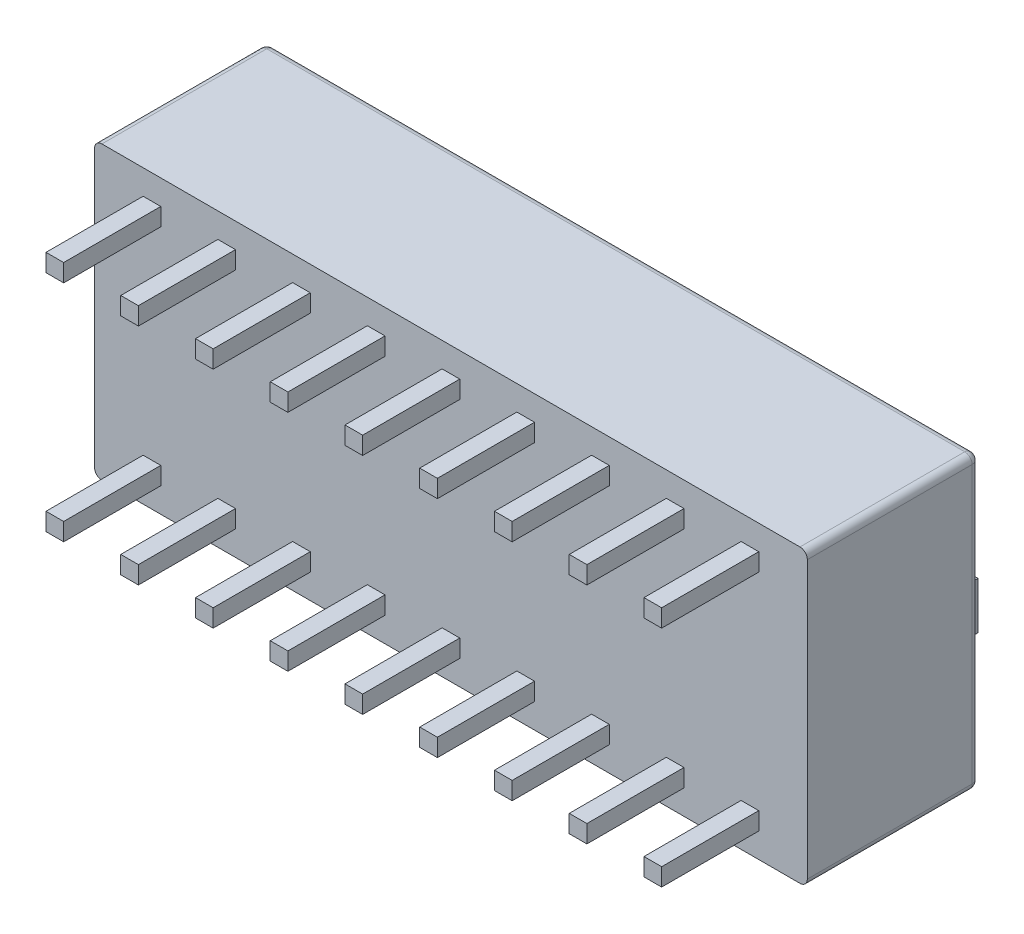
SolidWorks part; units mm, degrees
ref_plane "Ön Düzlem" through (0, 0, 0) normal (0, 0, 1) x (1, 0, 0)
ref_plane "Üst Düzlem" through (0, 0, 0) normal (0, 1, 0) x (1, 0, 0)
ref_plane "Sağ Düzlem" through (0, 0, 0) normal (1, 0, 0) x (0, 0, -1)
sketch "Çizim1" plane through (0, 0, 0) normal (0, 0, 1) x (1, 0, 0)
  line L1 (-12.11, 4.95) -> (12.11, 4.95)
  line L2 (-12.11, 4.95) -> (-12.11, -4.95)
  line L3 (-12.11, -4.95) -> (12.11, -4.95)
  line L4 (12.11, 4.95) -> (12.11, -4.95)
  line L5 (-12.11, 4.95) -> (12.11, -4.95) construction
  line L6 (-12.11, -4.95) -> (12.11, 4.95) construction
  point P0 (0, 0)
extrude "Yükseklik-Ekstrüzyon1" add sketch "Çizim1" along normal blind 5.85
sketch "Çizim3" plane through (0, 0, 0) normal (0, 0, -1) x (-1, 0, 0)
  line L10 (-10.86, 1.6) -> (-9.46, 1.6)
  line L11 (-10.86, 1.6) -> (-10.86, -1.6)
  line L12 (-10.86, -1.6) -> (-9.46, -1.6)
  line L13 (-9.46, 1.6) -> (-9.46, -1.6)
  line L14 (-10.86, 1.6) -> (-9.46, -1.6) construction
  line L15 (-10.86, -1.6) -> (-9.46, 1.6) construction
  line L16 (-8.32, 1.6) -> (-6.92, 1.6)
  line L17 (-8.32, 1.6) -> (-8.32, -1.6)
  line L18 (-8.32, -1.6) -> (-6.92, -1.6)
  line L19 (-6.92, 1.6) -> (-6.92, -1.6)
  line L20 (-8.32, 1.6) -> (-6.92, -1.6) construction
  line L21 (-8.32, -1.6) -> (-6.92, 1.6) construction
  line L22 (-5.78, 1.6) -> (-4.38, 1.6)
  line L23 (-5.78, 1.6) -> (-5.78, -1.6)
  line L24 (-5.78, -1.6) -> (-4.38, -1.6)
  line L25 (-4.38, 1.6) -> (-4.38, -1.6)
  line L26 (-5.78, 1.6) -> (-4.38, -1.6) construction
  line L27 (-5.78, -1.6) -> (-4.38, 1.6) construction
  line L28 (-3.24, 1.6) -> (-1.84, 1.6)
  line L29 (-3.24, 1.6) -> (-3.24, -1.6)
  line L30 (-3.24, -1.6) -> (-1.84, -1.6)
  line L31 (-1.84, 1.6) -> (-1.84, -1.6)
  line L32 (-3.24, 1.6) -> (-1.84, -1.6) construction
  line L33 (-3.24, -1.6) -> (-1.84, 1.6) construction
  line L34 (-0.7, 1.6) -> (0.7, 1.6)
  line L35 (-0.7, 1.6) -> (-0.7, -1.6)
  line L36 (-0.7, -1.6) -> (0.7, -1.6)
  line L37 (0.7, 1.6) -> (0.7, -1.6)
  line L38 (-0.7, 1.6) -> (0.7, -1.6) construction
  line L39 (-0.7, -1.6) -> (0.7, 1.6) construction
  line L40 (1.84, 1.6) -> (3.24, 1.6)
  line L41 (1.84, 1.6) -> (1.84, -1.6)
  line L42 (1.84, -1.6) -> (3.24, -1.6)
  line L43 (3.24, 1.6) -> (3.24, -1.6)
  line L44 (1.84, 1.6) -> (3.24, -1.6) construction
  line L45 (1.84, -1.6) -> (3.24, 1.6) construction
  line L46 (4.38, 1.6) -> (5.78, 1.6)
  line L47 (4.38, 1.6) -> (4.38, -1.6)
  line L48 (4.38, -1.6) -> (5.78, -1.6)
  line L49 (5.78, 1.6) -> (5.78, -1.6)
  line L50 (4.38, 1.6) -> (5.78, -1.6) construction
  line L51 (4.38, -1.6) -> (5.78, 1.6) construction
  line L52 (6.92, 1.6) -> (8.32, 1.6)
  line L53 (6.92, 1.6) -> (6.92, -1.6)
  line L54 (6.92, -1.6) -> (8.32, -1.6)
  line L55 (8.32, 1.6) -> (8.32, -1.6)
  line L56 (6.92, 1.6) -> (8.32, -1.6) construction
  line L57 (6.92, -1.6) -> (8.32, 1.6) construction
  line L58 (9.46, 1.6) -> (10.86, 1.6)
  line L59 (9.46, 1.6) -> (9.46, -1.6)
  line L60 (9.46, -1.6) -> (10.86, -1.6)
  line L61 (10.86, 1.6) -> (10.86, -1.6)
  line L62 (9.46, 1.6) -> (10.86, -1.6) construction
  line L63 (9.46, -1.6) -> (10.86, 1.6) construction
extrude "Kes-Ekstrüzyon1" cut sketch "Çizim3" against normal blind 1
sketch "Çizim5" plane through (0, 0, 1) normal (0, 0, -1) x (-1, 0, 0)
  line L0 (-9.46, -1.6) -> (-9.46, 1.6) construction
  line L1 (-10.86, -1.6) -> (-9.46, -1.6)
  line L2 (-10.86, -1.6) -> (-10.86, 0)
  line L3 (-10.86, 0) -> (-9.46, 0)
  line L4 (-9.46, -1.6) -> (-9.46, 0)
  line L5 (-8.32, 1.6) -> (-8.32, -1.6) construction
  line L6 (-8.32, 0) -> (-6.92, 0)
  line L7 (-8.32, 0) -> (-8.32, -1.6)
  line L8 (-8.32, -1.6) -> (-6.92, -1.6)
  line L9 (-6.92, 0) -> (-6.92, -1.6)
  line L10 (-5.78, 1.6) -> (-5.78, -1.6) construction
  line L11 (-5.78, 0) -> (-4.38, 0)
  line L12 (-5.78, 0) -> (-5.78, -1.6)
  line L13 (-5.78, -1.6) -> (-4.38, -1.6)
  line L14 (-4.38, 0) -> (-4.38, -1.6)
  line L15 (-1.84, -1.6) -> (-1.84, 1.6) construction
  line L16 (-3.24, -1.6) -> (-1.84, -1.6)
  line L17 (-3.24, -1.6) -> (-3.24, 0)
  line L18 (-3.24, 0) -> (-1.84, 0)
  line L19 (-1.84, -1.6) -> (-1.84, 0)
  line L20 (-0.7, 1.6) -> (-0.7, -1.6) construction
  line L21 (-0.7, 0) -> (0.7, 0)
  line L22 (-0.7, 0) -> (-0.7, -1.6)
  line L23 (-0.7, -1.6) -> (0.7, -1.6)
  line L24 (0.7, 0) -> (0.7, -1.6)
  line L25 (3.24, -1.6) -> (3.24, 1.6) construction
  line L26 (1.84, -1.6) -> (3.24, -1.6)
  line L27 (1.84, -1.6) -> (1.84, 0)
  line L28 (1.84, 0) -> (3.24, 0)
  line L29 (3.24, -1.6) -> (3.24, 0)
  line L30 (5.78, -1.6) -> (5.78, 1.6) construction
  line L31 (4.38, -1.6) -> (5.78, -1.6)
  line L32 (4.38, -1.6) -> (4.38, 0)
  line L33 (4.38, 0) -> (5.78, 0)
  line L34 (5.78, -1.6) -> (5.78, 0)
  line L35 (6.92, 1.6) -> (6.92, -1.6) construction
  line L36 (6.92, 0) -> (8.32, 0)
  line L37 (6.92, 0) -> (6.92, -1.6)
  line L38 (6.92, -1.6) -> (8.32, -1.6)
  line L39 (8.32, 0) -> (8.32, -1.6)
  line L40 (10.86, -1.6) -> (10.86, 1.6) construction
  line L41 (9.46, -1.6) -> (10.86, -1.6)
  line L42 (9.46, -1.6) -> (9.46, 0)
  line L43 (9.46, 0) -> (10.86, 0)
  line L44 (10.86, -1.6) -> (10.86, 0)
extrude "Yükseklik-Ekstrüzyon2" add sketch "Çizim5" along normal blind 2.2 separate body
sketch "Çizim6" plane through (0, 0, 1) normal (0, 0, -1) x (-1, 0, 0)
  line L0 (-9.46, -1.6) -> (-9.46, 1.6) construction
  line L1 (-10.86, 1.6) -> (-9.46, 1.6)
  line L2 (-10.86, 1.6) -> (-10.86, 0)
  line L3 (-10.86, 0) -> (-9.46, 0)
  line L4 (-9.46, 1.6) -> (-9.46, 0)
  line L5 (-0.7, 1.6) -> (-0.7, -1.6) construction
  line L6 (-8.32, 0) -> (-6.92, 0)
  line L7 (-8.32, 0) -> (-8.32, 1.6)
  line L8 (-8.32, 1.6) -> (-6.92, 1.6)
  line L9 (-6.92, 0) -> (-6.92, 1.6)
  line L10 (-5.78, 1.6) -> (-4.38, 1.6)
  line L11 (-5.78, 1.6) -> (-5.78, 0)
  line L12 (-5.78, 0) -> (-4.38, 0)
  line L13 (-4.38, 1.6) -> (-4.38, 0)
  line L14 (-3.24, 1.6) -> (-1.84, 1.6)
  line L15 (-3.24, 1.6) -> (-3.24, 0)
  line L16 (-3.24, 0) -> (-1.84, 0)
  line L17 (-1.84, 1.6) -> (-1.84, 0)
  line L18 (-0.7, 0) -> (0.7, 0)
  line L19 (-0.7, 0) -> (-0.7, 1.6)
  line L20 (-0.7, 1.6) -> (0.7, 1.6)
  line L21 (0.7, 0) -> (0.7, 1.6)
  line L22 (3.24, -1.6) -> (3.24, 1.6) construction
  line L23 (1.84, 1.6) -> (3.24, 1.6)
  line L24 (1.84, 1.6) -> (1.84, 0)
  line L25 (1.84, 0) -> (3.24, 0)
  line L26 (3.24, 1.6) -> (3.24, 0)
  line L27 (6.92, 1.6) -> (6.92, -1.6) construction
  line L28 (4.38, 1.6) -> (5.78, 1.6)
  line L29 (4.38, 1.6) -> (4.38, 0)
  line L30 (4.38, 0) -> (5.78, 0)
  line L31 (5.78, 1.6) -> (5.78, 0)
  line L32 (6.92, 0) -> (8.32, 0)
  line L33 (6.92, 0) -> (6.92, 1.6)
  line L34 (6.92, 1.6) -> (8.32, 1.6)
  line L35 (8.32, 0) -> (8.32, 1.6)
  line L37 (9.46, 1.6) -> (10.86, 1.6)
  line L38 (9.46, 1.6) -> (9.46, 0)
  line L39 (9.46, 0) -> (10.86, 0)
  line L40 (10.86, 1.6) -> (10.86, 0)
extrude "Yükseklik-Ekstrüzyon3" add sketch "Çizim6" along normal blind 0.9 separate body
fillet "Radyus1" radius 0.25 8 edges at (12.11, -4.95, 2.925) (12.11, 4.95, 2.925) (-12.11, -4.95, 2.925) (12.11, 0, 0) (0, -4.95, 0) (0, 4.95, 0) (-12.11, 0, 0) (-12.11, 4.95, 2.925)
sketch "Çizim7" plane through (0, 0, 5.85) normal (0, 0, 1) x (1, 0, 0)
  line L19 (-10.46, 4.11) -> (-9.86, 4.11)
  line L20 (-10.46, 4.11) -> (-10.46, 3.51)
  line L21 (-10.46, 3.51) -> (-9.86, 3.51)
  line L22 (-9.86, 4.11) -> (-9.86, 3.51)
  line L23 (-10.46, 4.11) -> (-9.86, 3.51) construction
  line L24 (-10.46, 3.51) -> (-9.86, 4.11) construction
  line L25 (-7.92, 4.11) -> (-7.32, 4.11)
  line L26 (-7.92, 4.11) -> (-7.92, 3.51)
  line L27 (-7.92, 3.51) -> (-7.32, 3.51)
  line L28 (-7.32, 4.11) -> (-7.32, 3.51)
  line L29 (-7.92, 4.11) -> (-7.32, 3.51) construction
  line L30 (-7.92, 3.51) -> (-7.32, 4.11) construction
  line L31 (-5.38, 4.11) -> (-4.78, 4.11)
  line L32 (-5.38, 4.11) -> (-5.38, 3.51)
  line L33 (-5.38, 3.51) -> (-4.78, 3.51)
  line L34 (-4.78, 4.11) -> (-4.78, 3.51)
  line L35 (-5.38, 4.11) -> (-4.78, 3.51) construction
  line L36 (-5.38, 3.51) -> (-4.78, 4.11) construction
  line L37 (-2.84, 4.11) -> (-2.24, 4.11)
  line L38 (-2.84, 4.11) -> (-2.84, 3.51)
  line L39 (-2.84, 3.51) -> (-2.24, 3.51)
  line L40 (-2.24, 4.11) -> (-2.24, 3.51)
  line L41 (-2.84, 4.11) -> (-2.24, 3.51) construction
  line L42 (-2.84, 3.51) -> (-2.24, 4.11) construction
  line L43 (-0.3, 4.11) -> (0.3, 4.11)
  line L44 (-0.3, 4.11) -> (-0.3, 3.51)
  line L45 (-0.3, 3.51) -> (0.3, 3.51)
  line L46 (0.3, 4.11) -> (0.3, 3.51)
  line L47 (-0.3, 4.11) -> (0.3, 3.51) construction
  line L48 (-0.3, 3.51) -> (0.3, 4.11) construction
  line L49 (2.24, 4.11) -> (2.84, 4.11)
  line L50 (2.24, 4.11) -> (2.24, 3.51)
  line L51 (2.24, 3.51) -> (2.84, 3.51)
  line L52 (2.84, 4.11) -> (2.84, 3.51)
  line L53 (2.24, 4.11) -> (2.84, 3.51) construction
  line L54 (2.24, 3.51) -> (2.84, 4.11) construction
  line L55 (4.78, 4.11) -> (5.38, 4.11)
  line L56 (4.78, 4.11) -> (4.78, 3.51)
  line L57 (4.78, 3.51) -> (5.38, 3.51)
  line L58 (5.38, 4.11) -> (5.38, 3.51)
  line L59 (4.78, 4.11) -> (5.38, 3.51) construction
  line L60 (4.78, 3.51) -> (5.38, 4.11) construction
  line L61 (7.32, 4.11) -> (7.92, 4.11)
  line L62 (7.32, 4.11) -> (7.32, 3.51)
  line L63 (7.32, 3.51) -> (7.92, 3.51)
  line L64 (7.92, 4.11) -> (7.92, 3.51)
  line L65 (7.32, 4.11) -> (7.92, 3.51) construction
  line L66 (7.32, 3.51) -> (7.92, 4.11) construction
  line L67 (9.86, 4.11) -> (10.46, 4.11)
  line L68 (9.86, 4.11) -> (9.86, 3.51)
  line L69 (9.86, 3.51) -> (10.46, 3.51)
  line L70 (10.46, 4.11) -> (10.46, 3.51)
  line L71 (9.86, 4.11) -> (10.46, 3.51) construction
  line L72 (9.86, 3.51) -> (10.46, 4.11) construction
  line L73 (9.86, -4.11) -> (10.46, -4.11)
  line L74 (9.86, -4.11) -> (9.86, -3.51)
  line L75 (9.86, -3.51) -> (10.46, -3.51)
  line L76 (10.46, -4.11) -> (10.46, -3.51)
  line L77 (9.86, -4.11) -> (10.46, -3.51) construction
  line L78 (9.86, -3.51) -> (10.46, -4.11) construction
  line L79 (7.32, -4.11) -> (7.92, -4.11)
  line L80 (7.32, -4.11) -> (7.32, -3.51)
  line L81 (7.32, -3.51) -> (7.92, -3.51)
  line L82 (7.92, -4.11) -> (7.92, -3.51)
  line L83 (7.32, -4.11) -> (7.92, -3.51) construction
  line L84 (7.32, -3.51) -> (7.92, -4.11) construction
  line L85 (4.78, -4.11) -> (5.38, -4.11)
  line L86 (4.78, -4.11) -> (4.78, -3.51)
  line L87 (4.78, -3.51) -> (5.38, -3.51)
  line L88 (5.38, -4.11) -> (5.38, -3.51)
  line L89 (4.78, -4.11) -> (5.38, -3.51) construction
  line L90 (4.78, -3.51) -> (5.38, -4.11) construction
  line L91 (2.24, -4.11) -> (2.84, -4.11)
  line L92 (2.24, -4.11) -> (2.24, -3.51)
  line L93 (2.24, -3.51) -> (2.84, -3.51)
  line L94 (2.84, -4.11) -> (2.84, -3.51)
  line L95 (2.24, -4.11) -> (2.84, -3.51) construction
  line L96 (2.24, -3.51) -> (2.84, -4.11) construction
  line L97 (-0.3, -4.11) -> (0.3, -4.11)
  line L98 (-0.3, -4.11) -> (-0.3, -3.51)
  line L99 (-0.3, -3.51) -> (0.3, -3.51)
  line L100 (0.3, -4.11) -> (0.3, -3.51)
  line L101 (-0.3, -4.11) -> (0.3, -3.51) construction
  line L102 (-0.3, -3.51) -> (0.3, -4.11) construction
  line L103 (-2.84, -4.11) -> (-2.24, -4.11)
  line L104 (-2.84, -4.11) -> (-2.84, -3.51)
  line L105 (-2.84, -3.51) -> (-2.24, -3.51)
  line L106 (-2.24, -4.11) -> (-2.24, -3.51)
  line L107 (-2.84, -4.11) -> (-2.24, -3.51) construction
  line L108 (-2.84, -3.51) -> (-2.24, -4.11) construction
  line L109 (-5.38, -4.11) -> (-4.78, -4.11)
  line L110 (-5.38, -4.11) -> (-5.38, -3.51)
  line L111 (-5.38, -3.51) -> (-4.78, -3.51)
  line L112 (-4.78, -4.11) -> (-4.78, -3.51)
  line L113 (-5.38, -4.11) -> (-4.78, -3.51) construction
  line L114 (-5.38, -3.51) -> (-4.78, -4.11) construction
  line L115 (-7.92, -4.11) -> (-7.32, -4.11)
  line L116 (-7.92, -4.11) -> (-7.92, -3.51)
  line L117 (-7.92, -3.51) -> (-7.32, -3.51)
  line L118 (-7.32, -4.11) -> (-7.32, -3.51)
  line L119 (-7.92, -4.11) -> (-7.32, -3.51) construction
  line L120 (-7.92, -3.51) -> (-7.32, -4.11) construction
  line L121 (-10.46, -4.11) -> (-9.86, -4.11)
  line L122 (-10.46, -4.11) -> (-10.46, -3.51)
  line L123 (-10.46, -3.51) -> (-9.86, -3.51)
  line L124 (-9.86, -4.11) -> (-9.86, -3.51)
  line L125 (-10.46, -4.11) -> (-9.86, -3.51) construction
  line L126 (-10.46, -3.51) -> (-9.86, -4.11) construction
  point P110 (-9.86, 3.81)
  point P112 (-9.86, -3.81)
  point P113 (-4.78, -3.81)
extrude "Yükseklik-Ekstrüzyon4" add sketch "Çizim7" along normal blind 3.3
